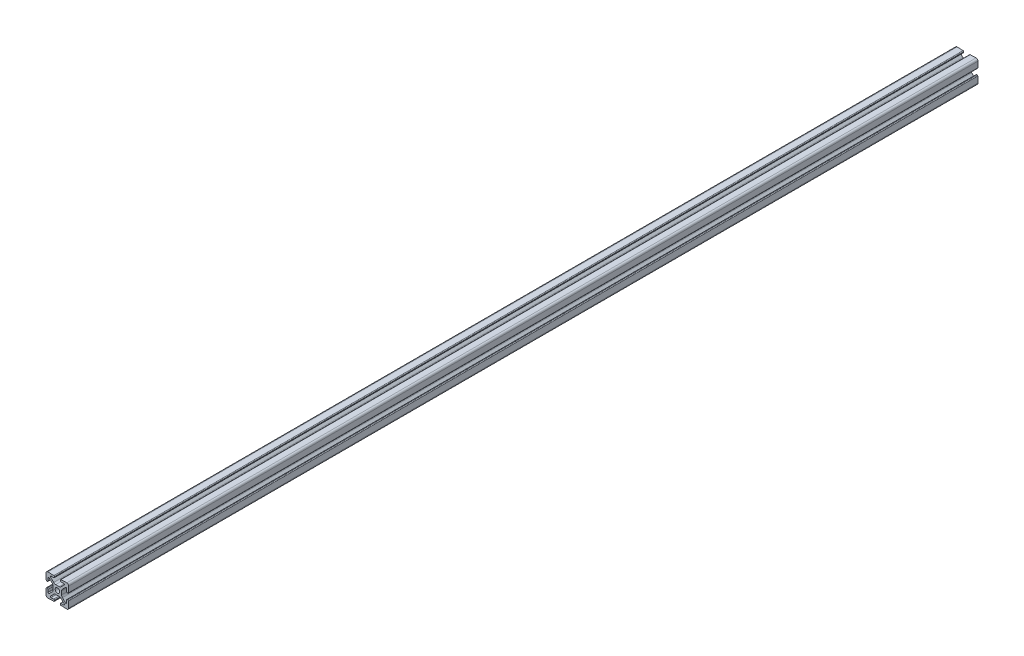
SolidWorks part; units mm, degrees
ref_plane "Front Plane" through (0, 0, 0) normal (0, 0, 1) x (1, 0, 0)
ref_plane "Top Plane" through (0, 0, 0) normal (0, 1, 0) x (1, 0, 0)
ref_plane "Right Plane" through (0, 0, 0) normal (1, 0, 0) x (0, 0, -1)
sketch "Sketch1" plane through (0, 0, 0) normal (0, 0, 1) x (1, 0, 0)
  line L0 (0, 0) -> (0, 12.7) construction
  line L1 (0, 0) -> (12.7, 0) construction
  line L2 (0, 0) -> (-12.7, 12.7) construction
  line L3 (-10.5971, 12.6988) -> (-3.9739, 12.4675)
  line L4 (-12.7, 12.7) -> (0, 12.7) construction
  line L6 (-4.0475, 10.3606) -> (-7.0332, 10.4648)
  line L10 (0, 4.7625) -> (-1.8848, 4.7625)
  line L11 (-4.1299, 5.6924) -> (-7.5996, 9.1622)
  line L24 (0, 0) -> (-12.7, 0) construction
  line L25 (-12.7, 0) -> (0, 0) construction
  line L26 (0, 0) -> (0, -12.7) construction
  line L27 (-12.7, -12.7) -> (-12.7, 12.7) construction
  line L28 (0, 12.7) -> (12.7, 12.7) construction
  line L29 (-3.239, 11.6793) -> (-3.2594, 11.0955)
  line L30 (-12.7, -12.7) -> (12.7, -12.7) construction
  arc A0 (-12.1048, 12.1048) -> (-10.5971, 12.6988) centre (-10.668, 10.668) cw
  arc A6 (-1.8848, 4.7625) -> (-4.1299, 5.6924) centre (-1.8848, 7.9375) cw
  circle A16 centre (0, 0) radius 2.54
  arc A18 (-7.5996, 9.1622) -> (-7.0332, 10.4648) centre (-7.0599, 9.702) cw
  circle A19 centre (-2.3794, 2.3794) radius 0.635 construction
  arc A20 (-4.0475, 10.3606) -> (-3.2594, 11.0955) centre (-4.0209, 11.1221) ccw
  arc A21 (-3.9739, 12.4675) -> (-3.239, 11.6793) centre (-4.0005, 11.7059) cw
  point P15 (0, 0)
  point P42 (-3.1999, 4.7625)
  point P80 (-12.7, 0)
  point P85 (0, -12.7)
  point P88 (0, -12.7)
  dimension "D11" = 2.032
  dimension "D15" = 3.175
  dimension "Center Hole Diameter" = 5.08
  dimension "D6" = 1.27
  dimension "D4" = 0.7633
  dimension "D8" = 0.762
  dimension "D12" = 0.762
  dimension "D1" = 45
  dimension "D2" = 2
  dimension "Rail Width" = 25.4
  dimension "D10" = 2.2098
  dimension "T-Slot Depth" = 7.9375
  dimension "D9" = 2.1082
  dimension "Rail Height" = 25.4
  dimension "D23" = 9.525
  dimension "D5" = 15.6464
  dimension "D3" = 4
  dimension "D7" = 5.7028
  dimension "T-Slot Width" = 6.477
sketch "Sketch2" plane through (0, 0, 0) normal (1, 0, 0) x (0, 0, -1)
  line L0 (-457.2, 0) -> (457.2, 0)
  line L2 (0, 0) -> (0, 12.7) construction
  line L3 (0, 0) -> (0, 12.7) construction
  point P0 (-419.1, 0)
  point P3 (0, 0)
  point P7 (419.1, 0)
  dimension "D1" = 38.1
  dimension "Length" = 914.4
sketch "Sketch3" plane through (0, 0, 0) normal (0, 0, 1) x (1, 0, 0)
  line L2 (0, 4.7625) -> (-1.8848, 4.7625) construction
  line L5 (-4.1299, 5.6924) -> (-7.5996, 9.1622) construction
  line L6 (-4.0475, 10.3606) -> (-7.0332, 10.4648) construction
  line L7 (-3.239, 11.6793) -> (-3.2594, 11.0955) construction
  line L67 (-10.5971, 12.6988) -> (-3.9739, 12.4675) construction
  line L68 (0, 4.7625) -> (-1.8848, 4.7625)
  line L69 (-4.1299, 5.6924) -> (-7.5996, 9.1622)
  line L70 (-4.0475, 10.3606) -> (-7.0332, 10.4648)
  line L71 (-3.239, 11.6793) -> (-3.2594, 11.0955)
  line L72 (-10.5971, 12.6988) -> (-3.9739, 12.4675)
  line L73 (0, 0) -> (-12.7, 12.7) construction
  line L74 (0, 0) -> (-12.7, 12.7) construction
  line L75 (-12.6988, 10.5971) -> (-12.4675, 3.9739)
  line L76 (-11.6793, 3.239) -> (-11.0955, 3.2594)
  line L77 (-10.3606, 4.0475) -> (-10.4648, 7.0332)
  line L78 (-5.6924, 4.1299) -> (-9.1622, 7.5996)
  line L79 (-4.7625, 0) -> (-4.7625, 1.8848)
  line L80 (-4.7625, 0) -> (-2.54, 0)
  line L82 (0, 4.7625) -> (0, 2.54)
  arc A3 (-4.1299, 5.6924) -> (-1.8848, 4.7625) centre (-1.8848, 7.9375) ccw construction
  circle A10 centre (0, 0) radius 2.54
  arc A56 (0, 2.54) -> (-2.54, 0) centre (0, 0) ccw
  arc A57 (-7.0332, 10.4648) -> (-7.5996, 9.1622) centre (-7.0599, 9.702) ccw construction
  arc A58 (-4.0475, 10.3606) -> (-3.2594, 11.0955) centre (-4.0209, 11.1221) ccw construction
  arc A59 (-3.239, 11.6793) -> (-3.9739, 12.4675) centre (-4.0005, 11.7059) ccw construction
  arc A60 (-10.5971, 12.6988) -> (-12.1048, 12.1048) centre (-10.668, 10.668) ccw construction
  arc A61 (-4.1299, 5.6924) -> (-1.8848, 4.7625) centre (-1.8848, 7.9375) ccw
  arc A62 (-7.0332, 10.4648) -> (-7.5996, 9.1622) centre (-7.0599, 9.702) ccw
  arc A63 (-4.0475, 10.3606) -> (-3.2594, 11.0955) centre (-4.0209, 11.1221) ccw
  arc A64 (-3.239, 11.6793) -> (-3.9739, 12.4675) centre (-4.0005, 11.7059) ccw
  arc A65 (-10.5971, 12.6988) -> (-12.6988, 10.5971) centre (-10.668, 10.668) ccw
  arc A67 (-11.6793, 3.239) -> (-12.4675, 3.9739) centre (-11.7059, 4.0005) cw
  arc A68 (-10.3606, 4.0475) -> (-11.0955, 3.2594) centre (-11.1221, 4.0209) cw
  arc A69 (-10.4648, 7.0332) -> (-9.1622, 7.5996) centre (-9.702, 7.0599) cw
  arc A70 (-5.6924, 4.1299) -> (-4.7625, 1.8848) centre (-7.9375, 1.8848) cw
  dimension "D1" = 0
extrude "Boss-Extrude1" add sketch "Sketch3" along normal mid plane 914.4
pattern_circular "CirPattern1" count 4 over 360 about axis through (0, 0, 0) along (0, 0, 1) of "Boss-Extrude1"
ref_plane "Contact Plane 1" through (0, 12.7, 0) normal (0, 1, 0) x (1, 0, 0)
ref_plane "Contact Plane 2" through (12.7, 0, 0) normal (1, 0, 0) x (0, 0, -1)
ref_plane "Contact Plane 3" through (0, -12.7, 0) normal (0, -1, 0) x (-1, 0, 0)
ref_plane "Contact Plane 4" through (-12.7, 0, 0) normal (-1, 0, 0) x (0, 0, 1)
sketch "Sketch4" plane through (0, 0, 457.2) normal (0, 0, 1) x (1, 0, 0)
  line L36 (1.8848, 4.7625) -> (-1.8848, 4.7625)
  line L37 (-4.1299, 5.6924) -> (-7.5996, 9.1622)
  line L38 (-7.0332, 10.4648) -> (-4.0475, 10.3606)
  line L39 (-3.2594, 11.0955) -> (-3.239, 11.6793)
  line L40 (-3.9739, 12.4675) -> (-10.5971, 12.6988)
  line L41 (-12.6988, 10.5971) -> (-12.4675, 3.9739)
  line L42 (-11.6793, 3.239) -> (-11.0955, 3.2594)
  line L43 (-10.3606, 4.0475) -> (-10.4648, 7.0332)
  line L44 (-9.1622, 7.5996) -> (-5.6924, 4.1299)
  line L45 (-4.7625, 1.8848) -> (-4.7625, -1.8848)
  line L46 (-5.6924, -4.1299) -> (-9.1622, -7.5996)
  line L47 (-10.4648, -7.0332) -> (-10.3606, -4.0475)
  line L48 (-11.0955, -3.2594) -> (-11.6793, -3.239)
  line L49 (-12.4675, -3.9739) -> (-12.6988, -10.5971)
  line L50 (-10.5971, -12.6988) -> (-3.9739, -12.4675)
  line L51 (-3.239, -11.6793) -> (-3.2594, -11.0955)
  line L52 (-4.0475, -10.3606) -> (-7.0332, -10.4648)
  line L53 (-7.5996, -9.1622) -> (-4.1299, -5.6924)
  line L54 (-1.8848, -4.7625) -> (1.8848, -4.7625)
  line L55 (4.1299, -5.6924) -> (7.5996, -9.1622)
  line L56 (7.0332, -10.4648) -> (4.0475, -10.3606)
  line L57 (3.2594, -11.0955) -> (3.239, -11.6793)
  line L58 (3.9739, -12.4675) -> (10.5971, -12.6988)
  line L59 (12.6988, -10.5971) -> (12.4675, -3.9739)
  line L60 (11.6793, -3.239) -> (11.0955, -3.2594)
  line L61 (10.3606, -4.0475) -> (10.4648, -7.0332)
  line L62 (9.1622, -7.5996) -> (5.6924, -4.1299)
  line L63 (4.7625, -1.8848) -> (4.7625, 1.8848)
  line L64 (5.6924, 4.1299) -> (9.1622, 7.5996)
  line L65 (10.4648, 7.0332) -> (10.3606, 4.0475)
  line L66 (11.0955, 3.2594) -> (11.6793, 3.239)
  line L67 (12.4675, 3.9739) -> (12.6988, 10.5971)
  line L68 (10.5971, 12.6988) -> (3.9739, 12.4675)
  line L69 (3.239, 11.6793) -> (3.2594, 11.0955)
  line L70 (4.0475, 10.3606) -> (7.0332, 10.4648)
  line L71 (7.5996, 9.1622) -> (4.1299, 5.6924)
  line L72 (1.8848, 4.7625) -> (-1.8848, 4.7625)
  line L73 (-4.1299, 5.6924) -> (-7.5996, 9.1622)
  line L74 (-7.0332, 10.4648) -> (-4.0475, 10.3606)
  line L75 (-3.2594, 11.0955) -> (-3.239, 11.6793)
  line L76 (-3.9739, 12.4675) -> (-10.5971, 12.6988)
  line L77 (-12.6988, 10.5971) -> (-12.4675, 3.9739)
  line L78 (-11.6793, 3.239) -> (-11.0955, 3.2594)
  line L79 (-10.3606, 4.0475) -> (-10.4648, 7.0332)
  line L80 (-9.1622, 7.5996) -> (-5.6924, 4.1299)
  line L81 (-4.7625, 1.8848) -> (-4.7625, -1.8848)
  line L82 (-5.6924, -4.1299) -> (-9.1622, -7.5996)
  line L83 (-10.4648, -7.0332) -> (-10.3606, -4.0475)
  line L84 (-11.0955, -3.2594) -> (-11.6793, -3.239)
  line L85 (-12.4675, -3.9739) -> (-12.6988, -10.5971)
  line L86 (-10.5971, -12.6988) -> (-3.9739, -12.4675)
  line L87 (-3.239, -11.6793) -> (-3.2594, -11.0955)
  line L88 (-4.0475, -10.3606) -> (-7.0332, -10.4648)
  line L89 (-7.5996, -9.1622) -> (-4.1299, -5.6924)
  line L90 (-1.8848, -4.7625) -> (1.8848, -4.7625)
  line L91 (4.1299, -5.6924) -> (7.5996, -9.1622)
  line L92 (7.0332, -10.4648) -> (4.0475, -10.3606)
  line L93 (3.2594, -11.0955) -> (3.239, -11.6793)
  line L94 (3.9739, -12.4675) -> (10.5971, -12.6988)
  line L95 (12.6988, -10.5971) -> (12.4675, -3.9739)
  line L96 (11.6793, -3.239) -> (11.0955, -3.2594)
  line L97 (10.3606, -4.0475) -> (10.4648, -7.0332)
  line L98 (9.1622, -7.5996) -> (5.6924, -4.1299)
  line L99 (4.7625, -1.8848) -> (4.7625, 1.8848)
  line L100 (5.6924, 4.1299) -> (9.1622, 7.5996)
  line L101 (10.4648, 7.0332) -> (10.3606, 4.0475)
  line L102 (11.0955, 3.2594) -> (11.6793, 3.239)
  line L103 (12.4675, 3.9739) -> (12.6988, 10.5971)
  line L104 (10.5971, 12.6988) -> (3.9739, 12.4675)
  line L105 (3.239, 11.6793) -> (3.2594, 11.0955)
  line L106 (4.0475, 10.3606) -> (7.0332, 10.4648)
  line L107 (7.5996, 9.1622) -> (4.1299, 5.6924)
  circle A0 centre (0, 0) radius 2.54 construction
  circle A1 centre (0, 0) radius 2.54
  arc A36 (1.8848, 4.7625) -> (4.1299, 5.6924) centre (1.8848, 7.9375) ccw
  arc A37 (-4.1299, 5.6924) -> (-1.8848, 4.7625) centre (-1.8848, 7.9375) ccw
  arc A38 (-7.0332, 10.4648) -> (-7.5996, 9.1622) centre (-7.0599, 9.702) ccw
  arc A39 (-4.0475, 10.3606) -> (-3.2594, 11.0955) centre (-4.0209, 11.1221) ccw
  arc A40 (-3.239, 11.6793) -> (-3.9739, 12.4675) centre (-4.0005, 11.7059) ccw
  arc A41 (-10.5971, 12.6988) -> (-12.6988, 10.5971) centre (-10.668, 10.668) ccw
  arc A42 (-12.4675, 3.9739) -> (-11.6793, 3.239) centre (-11.7059, 4.0005) ccw
  arc A43 (-11.0955, 3.2594) -> (-10.3606, 4.0475) centre (-11.1221, 4.0209) ccw
  arc A44 (-9.1622, 7.5996) -> (-10.4648, 7.0332) centre (-9.702, 7.0599) ccw
  arc A45 (-4.7625, 1.8848) -> (-5.6924, 4.1299) centre (-7.9375, 1.8848) ccw
  arc A46 (-5.6924, -4.1299) -> (-4.7625, -1.8848) centre (-7.9375, -1.8848) ccw
  arc A47 (-10.4648, -7.0332) -> (-9.1622, -7.5996) centre (-9.702, -7.0599) ccw
  arc A48 (-10.3606, -4.0475) -> (-11.0955, -3.2594) centre (-11.1221, -4.0209) ccw
  arc A49 (-11.6793, -3.239) -> (-12.4675, -3.9739) centre (-11.7059, -4.0005) ccw
  arc A50 (-12.6988, -10.5971) -> (-10.5971, -12.6988) centre (-10.668, -10.668) ccw
  arc A51 (-3.9739, -12.4675) -> (-3.239, -11.6793) centre (-4.0005, -11.7059) ccw
  arc A52 (-3.2594, -11.0955) -> (-4.0475, -10.3606) centre (-4.0209, -11.1221) ccw
  arc A53 (-7.5996, -9.1622) -> (-7.0332, -10.4648) centre (-7.0599, -9.702) ccw
  arc A54 (-1.8848, -4.7625) -> (-4.1299, -5.6924) centre (-1.8848, -7.9375) ccw
  arc A55 (4.1299, -5.6924) -> (1.8848, -4.7625) centre (1.8848, -7.9375) ccw
  arc A56 (7.0332, -10.4648) -> (7.5996, -9.1622) centre (7.0599, -9.702) ccw
  arc A57 (4.0475, -10.3606) -> (3.2594, -11.0955) centre (4.0209, -11.1221) ccw
  arc A58 (3.239, -11.6793) -> (3.9739, -12.4675) centre (4.0005, -11.7059) ccw
  arc A59 (10.5971, -12.6988) -> (12.6988, -10.5971) centre (10.668, -10.668) ccw
  arc A60 (12.4675, -3.9739) -> (11.6793, -3.239) centre (11.7059, -4.0005) ccw
  arc A61 (11.0955, -3.2594) -> (10.3606, -4.0475) centre (11.1221, -4.0209) ccw
  arc A62 (9.1622, -7.5996) -> (10.4648, -7.0332) centre (9.702, -7.0599) ccw
  arc A63 (4.7625, -1.8848) -> (5.6924, -4.1299) centre (7.9375, -1.8848) ccw
  arc A64 (5.6924, 4.1299) -> (4.7625, 1.8848) centre (7.9375, 1.8848) ccw
  arc A65 (10.4648, 7.0332) -> (9.1622, 7.5996) centre (9.702, 7.0599) ccw
  arc A66 (10.3606, 4.0475) -> (11.0955, 3.2594) centre (11.1221, 4.0209) ccw
  arc A67 (11.6793, 3.239) -> (12.4675, 3.9739) centre (11.7059, 4.0005) ccw
  arc A68 (12.6988, 10.5971) -> (10.5971, 12.6988) centre (10.668, 10.668) ccw
  arc A69 (3.9739, 12.4675) -> (3.239, 11.6793) centre (4.0005, 11.7059) ccw
  arc A70 (3.2594, 11.0955) -> (4.0475, 10.3606) centre (4.0209, 11.1221) ccw
  arc A71 (7.5996, 9.1622) -> (7.0332, 10.4648) centre (7.0599, 9.702) ccw
  arc A72 (1.8848, 4.7625) -> (4.1299, 5.6924) centre (1.8848, 7.9375) ccw
  arc A73 (-4.1299, 5.6924) -> (-1.8848, 4.7625) centre (-1.8848, 7.9375) ccw
  arc A74 (-7.0332, 10.4648) -> (-7.5996, 9.1622) centre (-7.0599, 9.702) ccw
  arc A75 (-4.0475, 10.3606) -> (-3.2594, 11.0955) centre (-4.0209, 11.1221) ccw
  arc A76 (-3.239, 11.6793) -> (-3.9739, 12.4675) centre (-4.0005, 11.7059) ccw
  arc A77 (-10.5971, 12.6988) -> (-12.6988, 10.5971) centre (-10.668, 10.668) ccw
  arc A78 (-12.4675, 3.9739) -> (-11.6793, 3.239) centre (-11.7059, 4.0005) ccw
  arc A79 (-11.0955, 3.2594) -> (-10.3606, 4.0475) centre (-11.1221, 4.0209) ccw
  arc A80 (-9.1622, 7.5996) -> (-10.4648, 7.0332) centre (-9.702, 7.0599) ccw
  arc A81 (-4.7625, 1.8848) -> (-5.6924, 4.1299) centre (-7.9375, 1.8848) ccw
  arc A82 (-5.6924, -4.1299) -> (-4.7625, -1.8848) centre (-7.9375, -1.8848) ccw
  arc A83 (-10.4648, -7.0332) -> (-9.1622, -7.5996) centre (-9.702, -7.0599) ccw
  arc A84 (-10.3606, -4.0475) -> (-11.0955, -3.2594) centre (-11.1221, -4.0209) ccw
  arc A85 (-11.6793, -3.239) -> (-12.4675, -3.9739) centre (-11.7059, -4.0005) ccw
  arc A86 (-12.6988, -10.5971) -> (-10.5971, -12.6988) centre (-10.668, -10.668) ccw
  arc A87 (-3.9739, -12.4675) -> (-3.239, -11.6793) centre (-4.0005, -11.7059) ccw
  arc A88 (-3.2594, -11.0955) -> (-4.0475, -10.3606) centre (-4.0209, -11.1221) ccw
  arc A89 (-7.5996, -9.1622) -> (-7.0332, -10.4648) centre (-7.0599, -9.702) ccw
  arc A90 (-1.8848, -4.7625) -> (-4.1299, -5.6924) centre (-1.8848, -7.9375) ccw
  arc A91 (4.1299, -5.6924) -> (1.8848, -4.7625) centre (1.8848, -7.9375) ccw
  arc A92 (7.0332, -10.4648) -> (7.5996, -9.1622) centre (7.0599, -9.702) ccw
  arc A93 (4.0475, -10.3606) -> (3.2594, -11.0955) centre (4.0209, -11.1221) ccw
  arc A94 (3.239, -11.6793) -> (3.9739, -12.4675) centre (4.0005, -11.7059) ccw
  arc A95 (10.5971, -12.6988) -> (12.6988, -10.5971) centre (10.668, -10.668) ccw
  arc A96 (12.4675, -3.9739) -> (11.6793, -3.239) centre (11.7059, -4.0005) ccw
  arc A97 (11.0955, -3.2594) -> (10.3606, -4.0475) centre (11.1221, -4.0209) ccw
  arc A98 (9.1622, -7.5996) -> (10.4648, -7.0332) centre (9.702, -7.0599) ccw
  arc A99 (4.7625, -1.8848) -> (5.6924, -4.1299) centre (7.9375, -1.8848) ccw
  arc A100 (5.6924, 4.1299) -> (4.7625, 1.8848) centre (7.9375, 1.8848) ccw
  arc A101 (10.4648, 7.0332) -> (9.1622, 7.5996) centre (9.702, 7.0599) ccw
  arc A102 (10.3606, 4.0475) -> (11.0955, 3.2594) centre (11.1221, 4.0209) ccw
  arc A103 (11.6793, 3.239) -> (12.4675, 3.9739) centre (11.7059, 4.0005) ccw
  arc A104 (12.6988, 10.5971) -> (10.5971, 12.6988) centre (10.668, 10.668) ccw
  arc A105 (3.9739, 12.4675) -> (3.239, 11.6793) centre (4.0005, 11.7059) ccw
  arc A106 (3.2594, 11.0955) -> (4.0475, 10.3606) centre (4.0209, 11.1221) ccw
  arc A107 (7.5996, 9.1622) -> (7.0332, 10.4648) centre (7.0599, 9.702) ccw
  dimension "D1" = 0
extrude "Boss-Extrude2" add sketch "Sketch4" along normal blind 101.6
equation "\"D1@Sketch2\"=\"Rail Width@Sketch1\"*1.5"
equation "\"D1@Boss-Extrude1\"=\"Length@Sketch2\""
